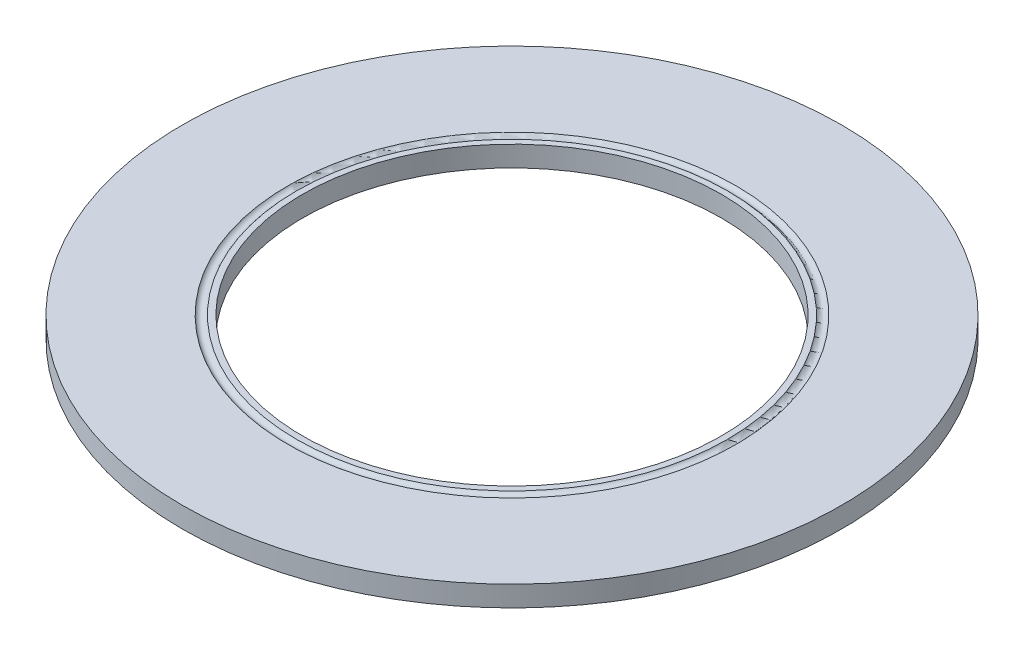
SolidWorks part; units mm, degrees
ref_plane "Front Plane" through (0, 0, 0) normal (0, 0, 1) x (1, 0, 0)
ref_plane "Top Plane" through (0, 0, 0) normal (0, 1, 0) x (1, 0, 0)
ref_plane "Right Plane" through (0, 0, 0) normal (1, 0, 0) x (0, 0, -1)
sketch "Sketch1" plane through (0, 0, 0) normal (0, 0, 1) x (1, 0, 0)
  line L0 (0, 0) -> (0, 42.5445) construction
  line L1 (-96.8375, 0) -> (-99.5857, 0)
  line L2 (-152.4, 0) -> (-152.4, 9.525)
  line L3 (-152.4, 9.525) -> (-103.6143, 9.525)
  line L4 (-96.8375, 0) -> (-96.8375, 9.525)
  line L5 (-96.8375, 9.525) -> (-99.5857, 9.525)
  line L6 (-99.5857, 0) -> (-103.6143, 0) construction
  line L7 (-103.6143, 0) -> (-152.4, 0)
  arc A0 (-103.6143, 9.525) -> (-99.5857, 9.525) centre (-101.6, 10.795) ccw
  arc A1 (-99.5857, 0) -> (-103.6143, 0) centre (-101.6, -1.27) ccw
  arc A2 (-103.6143, 0) -> (-99.5857, 0) centre (-101.6, -1.27) ccw construction
  arc A3 (-99.5857, 9.525) -> (-103.6143, 9.525) centre (-101.6, 10.795) ccw construction
  dimension "D1" = 4.7625
  dimension "D7" = 1.27
  dimension "D2" = 203.2
  dimension "D3" = 1.27
  dimension "D4" = 9.525
  dimension "D5" = 193.675
  dimension "D6" = 304.8
revolve "Revolve1" add sketch "Sketch1" angle 360 about L0
